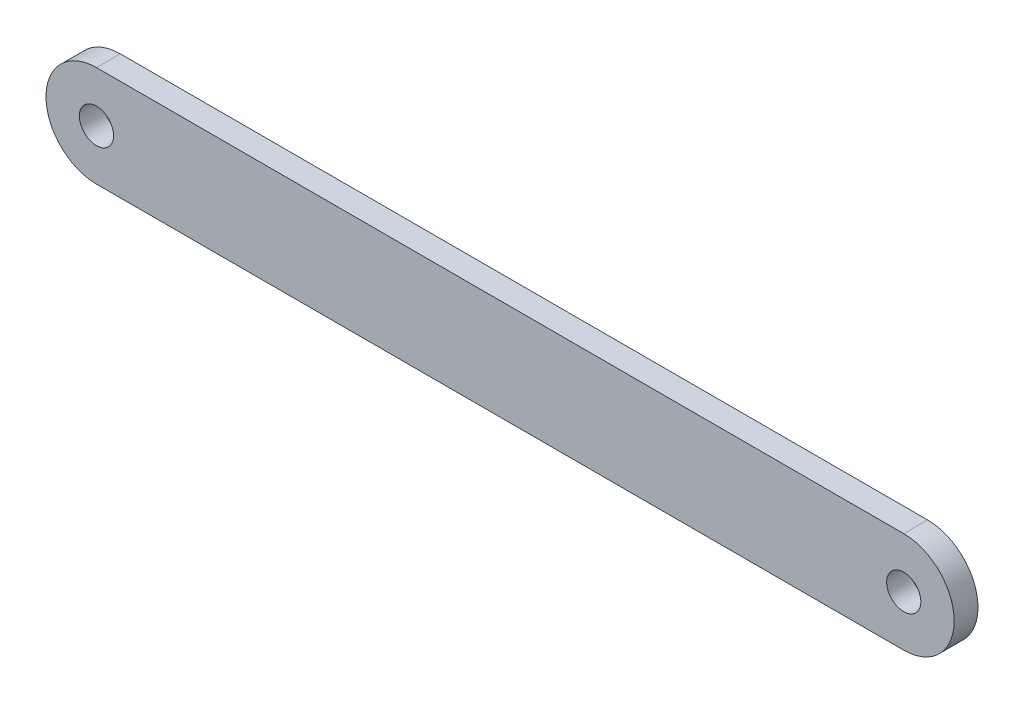
SolidWorks part; units mm, degrees
material "Custom Plastic"
ref_plane "Front Plane" through (0, 0, 0) normal (0, 0, 1) x (1, 0, 0)
ref_plane "Top Plane" through (0, 0, 0) normal (0, 1, 0) x (1, 0, 0)
ref_plane "Right Plane" through (0, 0, 0) normal (1, 0, 0) x (0, 0, -1)
sketch "Sketch1" plane through (0, 0, 0) normal (0, 0, 1) x (1, 0, 0)
  line L0 (-50.8, 0) -> (50.8, 0) construction
  line L1 (-50.8, 6.35) -> (50.8, 6.35)
  line L2 (-50.8, -6.35) -> (50.8, -6.35)
  arc A0 (-50.8, 6.35) -> (-50.8, -6.35) centre (-50.8, 0) ccw
  arc A1 (50.8, -6.35) -> (50.8, 6.35) centre (50.8, 0) ccw
  point P3 (0, 0)
  dimension "D1" = 6.35
  dimension "D2" = 101.6
extrude "Boss-Extrude1" add sketch "Sketch1" along normal blind 2.9972
hole_wizard "#8 Clearance Hole1" positions "Sketch3" profile "Sketch2" hole size "#8" standard "ANSI Inch"
sketch "Sketch3" plane through (0, 0, 2.9972) normal (0, 0, 1) x (1, 0, 0)
  point P0 (-50.8, 0)
  point P3 (50.8, 0)
sketch "Sketch2" plane through (-50.8, 0, 2.9972) normal (1, 0, 0) x (0, -1, 0)
  line L0 (0, 0) -> (0, 6.351)
  line L1 (0, 6.351) -> (2.1526, 6.351)
  line L2 (2.1526, 6.351) -> (2.1526, 0)
  line L5 (2.1526, 0) -> (0, 0)
  line L10 (0, 6.351) -> (-2.1526, 6.351) construction
  line L11 (0, -6.35) -> (0, 107.95) construction
  dimension "Hole Dia." = 4.3053
  dimension "Hole Depth" = 6.351
  dimension "Drill Angle" = 180
